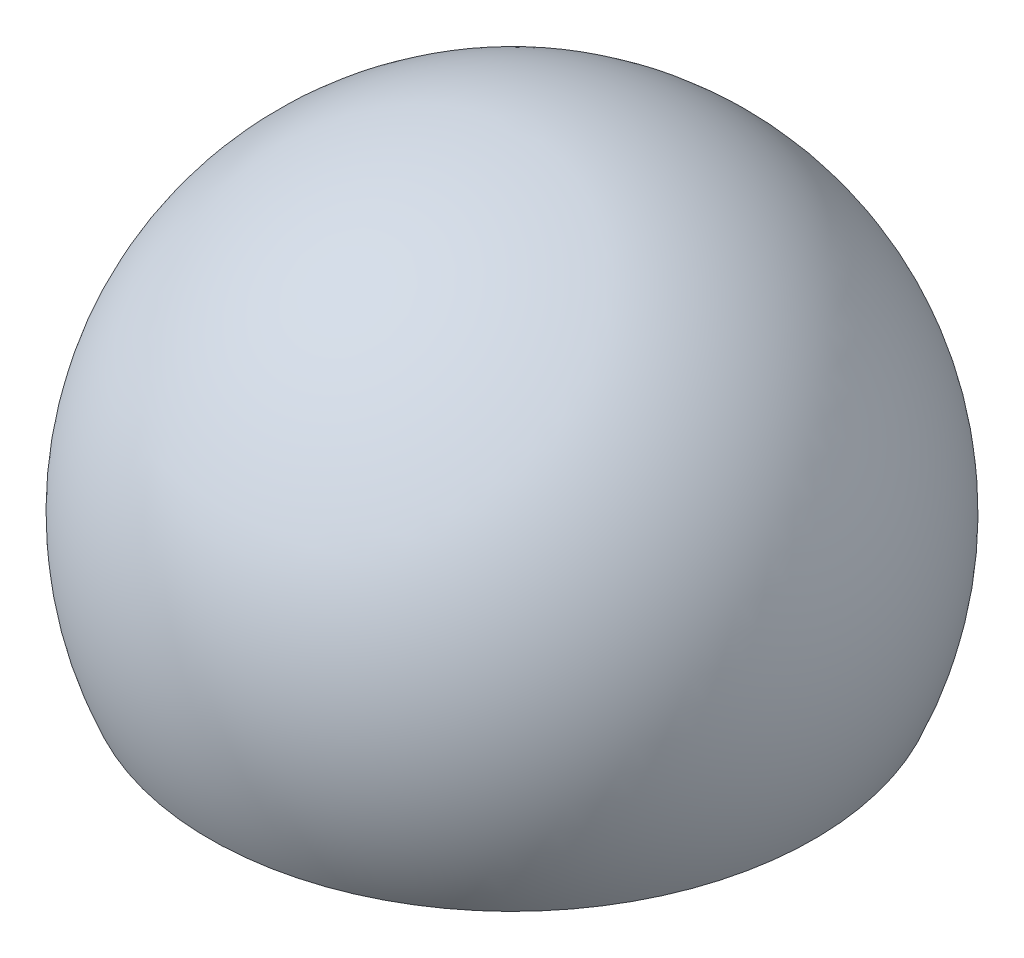
SolidWorks part; units mm, degrees
ref_plane "Front Plane" through (0, 0, 0) normal (0, 0, 1) x (1, 0, 0)
ref_plane "Top Plane" through (0, 0, 0) normal (0, 1, 0) x (1, 0, 0)
ref_plane "Right Plane" through (0, 0, 0) normal (1, 0, 0) x (0, 0, -1)
sketch "Sketch2" plane through (0, 0, 0) normal (0, 1, 0) x (1, 0, 0)
  line L1 (-5.49, 5.49) -> (5.49, 5.49)
  line L2 (-5.49, 5.49) -> (-5.49, -5.49)
  line L3 (-5.49, -5.49) -> (5.49, -5.49)
  line L4 (5.49, 5.49) -> (5.49, -5.49)
  line L5 (-5.49, 5.49) -> (5.49, -5.49) construction
  line L6 (-5.49, -5.49) -> (5.49, 5.49) construction
  point P0 (0, 0)
  dimension "D1" = 10.98
extrude "Boss-Extrude1" add sketch "Sketch2" along normal blind 10
fillet "Fillet1" radius 1 4 edges at (-5.49, 5, 5.49) (-5.49, 5, -5.49) (5.49, 5, -5.49) (5.49, 5, 5.49)
sketch "Sketch4" plane through (0, 0, 0) normal (1, 0, 0) x (0, 0, -1)
  line L0 (0, 10) -> (0, 35) construction
  line L1 (-4.49, 10) -> (4.49, 10) construction
  line L2 (-4.49, 0) -> (4.49, 0) construction
  line L3 (22.9129, 0) -> (11, 0)
  line L4 (5.49, 10) -> (5.49, 19.532)
  line L5 (0, 35) -> (0, 10)
  line L6 (0, 10) -> (5.49, 10)
  line L7 (11, 0) -> (11, 10)
  arc A0 (0, 35) -> (22.9129, 0) centre (0, 10) cw
  arc A2 (5.49, 19.532) -> (11, 10) centre (0, 10) cw
  point P10 (0, 0)
  point P15 (11.3445, 10)
  point P16 (0, 0)
  dimension "D2" = 25
  dimension "D1" = 11
revolve "Revolve1" add sketch "Sketch4" angle 360 about L0
equation "\"D1@Sketch2\"=11-0.02"
